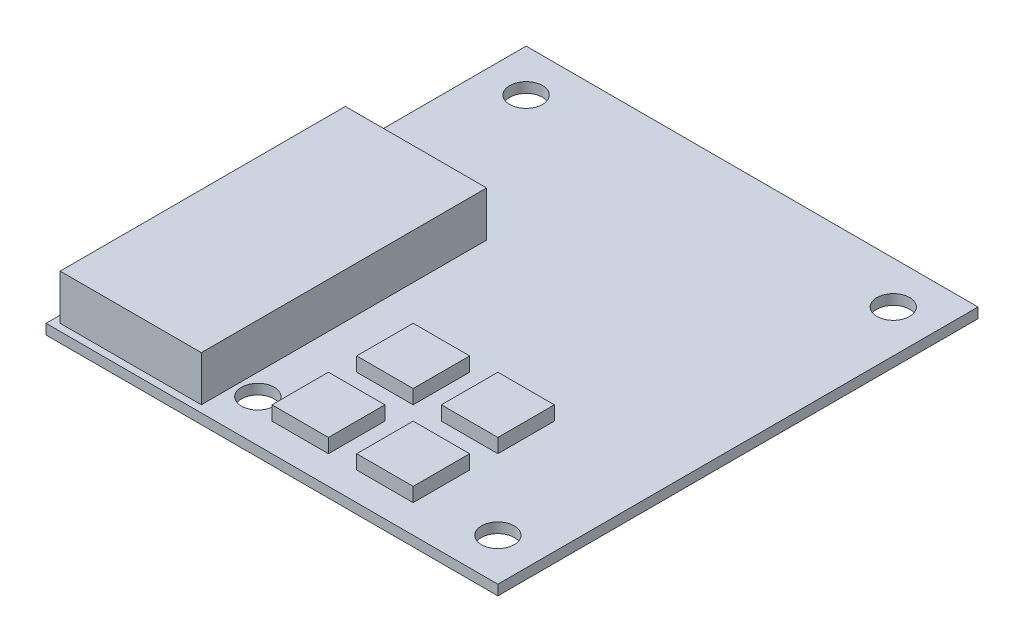
SolidWorks part; units mm, degrees
ref_plane "Front Plane" through (0, 0, 0) normal (0, 0, 1) x (1, 0, 0)
ref_plane "Top Plane" through (0, 0, 0) normal (0, 1, 0) x (1, 0, 0)
ref_plane "Right Plane" through (0, 0, 0) normal (1, 0, 0) x (0, 0, -1)
sketch "Sketch1" plane through (0, 0, 0) normal (0, 1, 0) x (1, 0, 0)
  line L1 (0, 0) -> (40.64, 0)
  line L2 (0, 0) -> (0, 43.18)
  line L3 (0, 43.18) -> (40.64, 43.18)
  line L4 (40.64, 0) -> (40.64, 43.18)
  dimension "D1" = 40.64
  dimension "D2" = 43.18
extrude "Boss-Extrude1" add sketch "Sketch1" along normal blind 0.9144
sketch "Sketch3" plane through (0, 0.9144, 0) normal (0, 1, 0) x (1, 0, 0)
  line L0 (0, 43.18) -> (0, 0) construction
  line L1 (17.78, 10.16) -> (22.86, 10.16)
  line L2 (17.78, 10.16) -> (17.78, 15.24)
  line L3 (17.78, 15.24) -> (22.86, 15.24)
  line L4 (22.86, 10.16) -> (22.86, 15.24)
  line L5 (17.78, 10.16) -> (22.86, 15.24) construction
  line L6 (17.78, 15.24) -> (22.86, 10.16) construction
  line L7 (0, 0) -> (40.64, 0) construction
  line L8 (30.48, 10.16) -> (30.48, 15.24)
  line L9 (25.4, 15.24) -> (30.48, 10.16) construction
  line L10 (25.4, 15.24) -> (30.48, 15.24)
  line L11 (25.4, 10.16) -> (25.4, 15.24)
  line L12 (25.4, 10.16) -> (30.48, 15.24) construction
  line L13 (25.4, 10.16) -> (30.48, 10.16)
  line L14 (30.48, 2.54) -> (30.48, 7.62)
  line L15 (25.4, 7.62) -> (30.48, 2.54) construction
  line L16 (25.4, 7.62) -> (30.48, 7.62)
  line L17 (25.4, 2.54) -> (25.4, 7.62)
  line L18 (25.4, 2.54) -> (30.48, 7.62) construction
  line L19 (25.4, 2.54) -> (30.48, 2.54)
  line L20 (22.86, 2.54) -> (22.86, 7.62)
  line L21 (17.78, 7.62) -> (22.86, 2.54) construction
  line L22 (17.78, 7.62) -> (22.86, 7.62)
  line L23 (17.78, 2.54) -> (17.78, 7.62)
  line L24 (17.78, 2.54) -> (22.86, 7.62) construction
  line L25 (17.78, 2.54) -> (22.86, 2.54)
  point P0 (20.32, 12.7)
  dimension "D1" = 20.32
  dimension "D2" = 12.7
  dimension "D3" = 5.08
  dimension "D4" = 2
  dimension "D5" = 2
extrude "Boss-Extrude2" add sketch "Sketch3" along normal blind 1.27
sketch "Sketch4" plane through (0, 0.9144, 0) normal (0, 1, 0) x (1, 0, 0)
  line L0 (0, 0) -> (40.64, 0) construction
  line L1 (0.635, 0.635) -> (13.335, 0.635)
  line L2 (0.635, 0.635) -> (0.635, 26.289)
  line L3 (0.635, 26.289) -> (13.335, 26.289)
  line L4 (13.335, 0.635) -> (13.335, 26.289)
  line L5 (0, 43.18) -> (0, 0) construction
  dimension "D1" = 0.635
  dimension "D2" = 0.635
  dimension "D3" = 25.654
  dimension "D4" = 12.7
extrude "Boss-Extrude3" add sketch "Sketch4" along normal blind 4.064
hole_wizard "#32 (0.116) Diameter Hole1" positions "Sketch7" profile "Sketch6" hole size "#32" standard "ANSI Inch"
sketch "Sketch7" plane through (0, 0.9144, 0) normal (0, 1, 0) x (1, 0, 0)
  line L0 (0, 0) -> (40.64, 0) construction
  line L1 (0, 43.18) -> (0, 0) construction
  point P0 (3.81, 39.37)
  point P2 (36.83, 39.37)
  point P4 (36.83, 3.81)
  point P6 (15.24, 3.81)
  dimension "D1" = 3.81
  dimension "D2" = 15.24
  dimension "D3" = 36.83
  dimension "D4" = 3.81
  dimension "D5" = 39.37
sketch "Sketch6" plane through (3.81, 0.9144, -39.37) normal (1, 0, 0) x (0, 0, 1)
  line L0 (0, 0) -> (0, 26.2852)
  line L1 (0, 26.2852) -> (1.4732, 25.4)
  line L2 (1.4732, 25.4) -> (1.4732, 0)
  line L5 (1.4732, 0) -> (0, 0)
  line L10 (0, 26.2852) -> (-1.4732, 25.4) construction
  line L11 (0, -6.35) -> (0, 107.95) construction
  dimension "Hole Dia." = 2.9464
  dimension "Hole Depth" = 25.4
  dimension "Drill Angle" = 118
